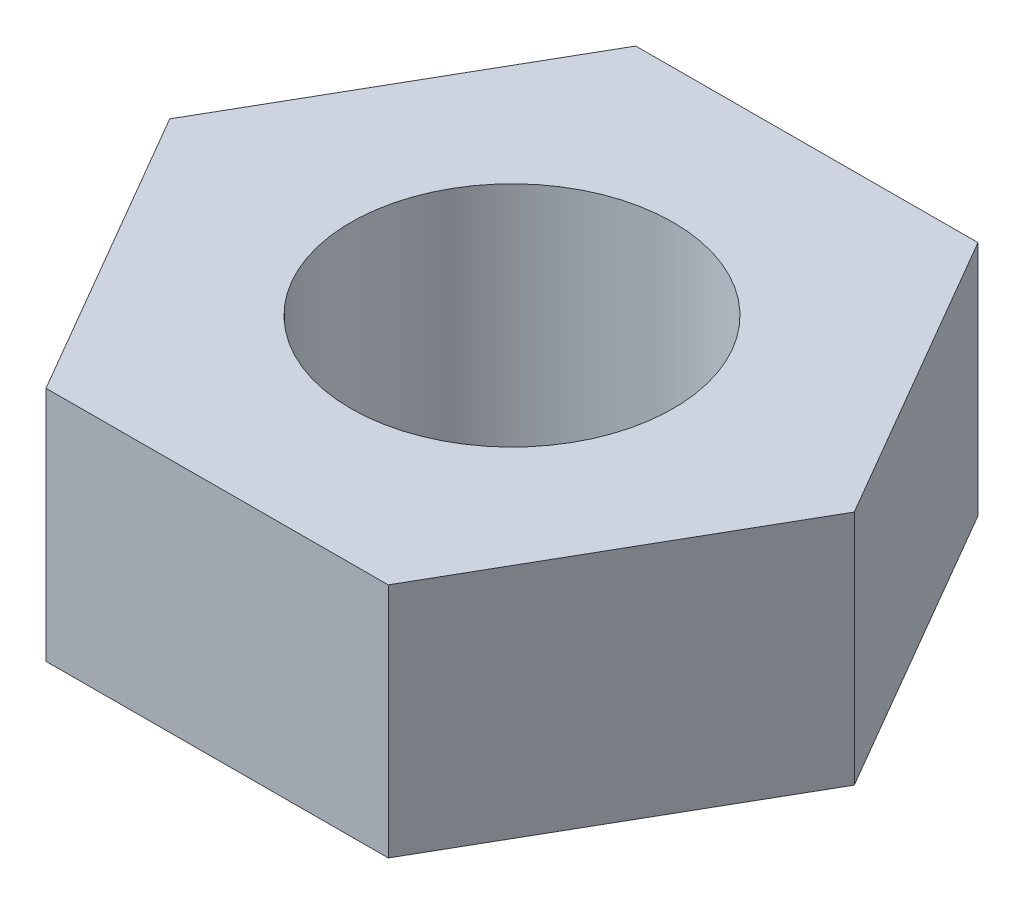
SolidWorks part; units mm, degrees
ref_plane "Front Plane" through (0, 0, 0) normal (0, 0, 1) x (1, 0, 0)
ref_plane "Top Plane" through (0, 0, 0) normal (0, 1, 0) x (1, 0, 0)
ref_plane "Right Plane" through (0, 0, 0) normal (1, 0, 0) x (0, 0, -1)
sketch "Sketch1" plane through (0, 0, 0) normal (0, 1, 0) x (1, 0, 0)
  line L1 (1.5806, 2.7541) -> (-1.5949, 2.7459)
  line L2 (-1.5949, 2.7459) -> (-3.1754, -0.0083)
  line L3 (-3.1754, -0.0083) -> (-1.5806, -2.7541)
  line L4 (-1.5806, -2.7541) -> (1.5949, -2.7459)
  line L5 (1.5949, -2.7459) -> (3.1754, 0.0083)
  line L6 (3.1754, 0.0083) -> (1.5806, 2.7541)
  circle A0 centre (0, 0) radius 2.75 construction
  circle A1 centre (0, 0) radius 1.5
  dimension "D2" = 3
  dimension "D1" = 5.5
extrude "Boss-Extrude1" add sketch "Sketch1" along normal blind 2.2
